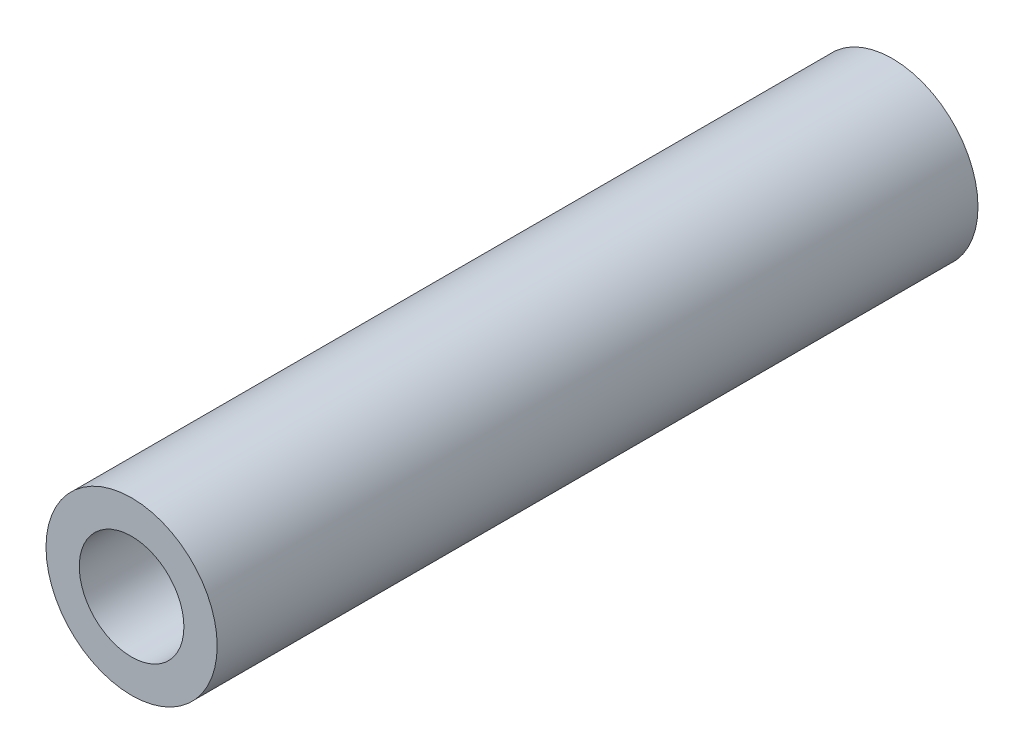
SolidWorks part; units mm, degrees
material "ABS"
ref_plane "前视基准面" through (0, 0, 0) normal (0, 0, 1) x (1, 0, 0)
ref_plane "上视基准面" through (0, 0, 0) normal (0, 1, 0) x (1, 0, 0)
ref_plane "右视基准面" through (0, 0, 0) normal (1, 0, 0) x (0, 0, -1)
other "Configuration Table"
sketch "草图1" plane through (0, 0, 0) normal (0, 0, 1) x (1, 0, 0)
  circle A0 centre (0, 0) radius 2.2
  circle A1 centre (0, 0) radius 3.6
  dimension "D1" = 4.4
  dimension "D2" = 1.4
extrude "凸台-拉伸1" add sketch "草图1" along normal mid plane 32
